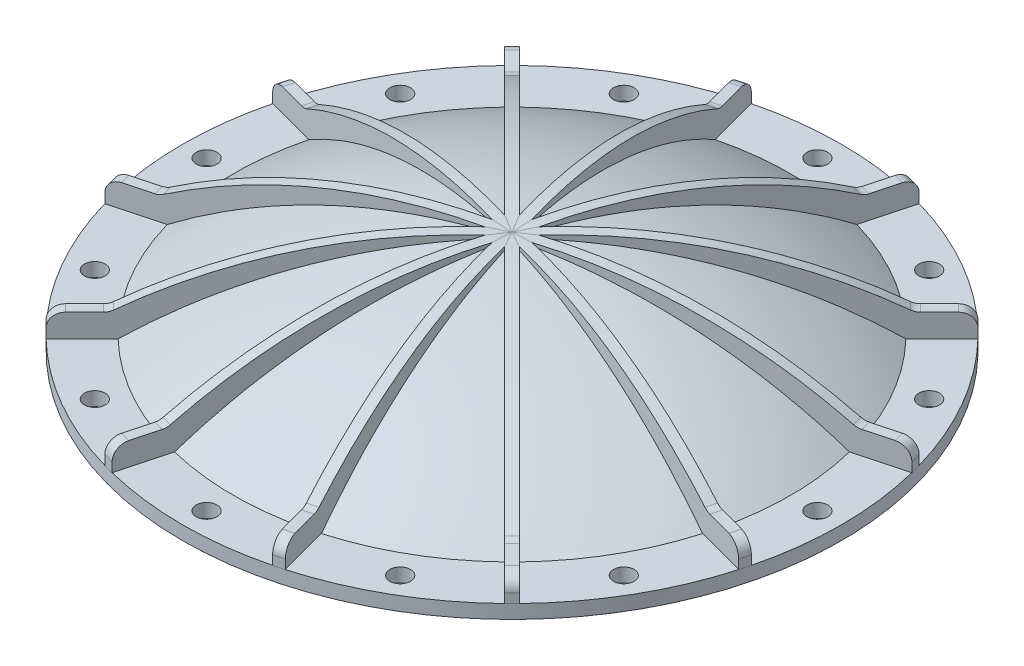
SolidWorks part; units mm, degrees
ref_plane "Front Plane" through (0, 0, 0) normal (0, 0, 1) x (1, 0, 0)
ref_plane "Top Plane" through (0, 0, 0) normal (0, 1, 0) x (1, 0, 0)
ref_plane "Right Plane" through (0, 0, 0) normal (1, 0, 0) x (0, 0, -1)
sketch "Sketch1" plane through (0, 0, 0) normal (0, 0, 1) x (1, 0, 0)
  line L0 (0, 0) -> (0, 65.6866) construction
  line L2 (151.84, 6.6196) -> (128.3759, 6.6196)
  arc A0 (124.8548, 7.6852) -> (2.4084, 46.7854) centre (-4.699, -186.7493) ccw
  arc A1 (128.3759, 6.6196) -> (124.8548, 7.6852) centre (128.3759, 12.9696) cw
  point P9 (126.44, 6.6196)
  dimension "D2" = 6.35
  dimension "D1" = 25.4
revolve "Revolve-Thin2" add sketch "Sketch1" angle 360 about L0
sketch "Sketch2" plane through (0, 0, 0) normal (0, 0, 1) x (1, 0, 0)
  line L0 (2.3304, 46.6898) -> (0, 46.6898)
  line L1 (0, 46.6898) -> (0, 62.1846) construction
revolve "Revolve-Thin3" add sketch "Sketch2" angle 360 about L1
sketch "Sketch4" plane through (0, 0, 0) normal (0, 0, 1) x (1, 0, 0)
  line L0 (0, 0) -> (0, 112.9727) construction
ref_plane "Plane1" through (0, 0, 0) normal (0.2588, 0, 0.9659) x (0.9659, 0, -0.2588)
sketch "Sketch5" plane through (0, 0, 0) normal (0.2588, 0, 0.9659) x (0.9659, 0, -0.2588)
  line L0 (151.84, 12.9696) -> (151.84, 17.2343)
  line L1 (145.49, 23.5843) -> (133.0255, 23.5843)
  line L2 (0, 0) -> (0, 112.9727) construction
  line L3 (151.84, 12.9696) -> (118.132, 12.9696)
  line L4 (151.84, 12.9696) -> (-151.84, 12.9696) construction
  line L5 (118.132, 12.9696) -> (94.1712, 28.0987)
  line L6 (94.1712, 28.0987) -> (45.2078, 45.1143)
  line L7 (45.2078, 45.1143) -> (0, 51.365)
  line L8 (0, 51.365) -> (0, 53.7958)
  arc A0 (0, 53.7958) -> (129.8768, 24.42) centre (16.8415, -173.5386) cw
  arc A1 (151.84, 17.2343) -> (145.49, 23.5843) centre (145.49, 17.2343) ccw
  arc A2 (133.0255, 23.5843) -> (129.8768, 24.42) centre (133.0255, 29.9343) cw
  dimension "D1" = 6.35
extrude "Extrude1" add sketch "Sketch5" along normal mid plane 4.7752
ref_plane "Plane2" through (0, 0, 0) normal (0.5, 0, 0.866) x (0.866, 0, -0.5)
mirror "Mirror1" about plane through (0, 0, 0) normal (0.5, 0, 0.866) of "Extrude1"
pattern_circular "CirPattern1" count 12 over 360 about axis through (0, 0, 0) along (0, 1, 0) of "Mirror1"
ref_plane "Plane3" through (0, 0, 0) normal (1, 0, 0) x (0, 0, -1)
sketch "Sketch6" plane through (0, 0, 0) normal (1, 0, 0) x (0, 0, -1)
  line L0 (0, 12.9696) -> (151.84, 12.9696) construction
  line L2 (30.9141, 12.9696) -> (-30.9141, 12.9696) construction
ref_plane "Plane4" through (0, 12.9696, 0) normal (0, 1, 0) x (-1, 0, 0)
sketch "Sketch7" plane through (0, 12.9696, 0) normal (0, 1, 0) x (-1, 0, 0)
  line L0 (0, 3.4322) -> (0, -140.7332) construction
  circle A0 centre (0, 0) radius 140.7332 construction
hole_wizard "3/8 (0.375) Diameter Hole1" positions "Sketch9" profile "Sketch8" hole size "3/8" standard "Ansi Inch"
sketch "Sketch9" plane through (0, 12.9696, 0) normal (0, 1, 0) x (-1, 0, 0)
  point P1 (0, -140.7332)
sketch "Sketch8" plane through (0, 12.9696, -140.7332) normal (1, 0, 0) x (0, 0, 1)
  line L0 (0, 0) -> (0, 28.2616)
  line L1 (0, 28.2616) -> (4.7625, 25.4)
  line L2 (4.7625, 25.4) -> (4.7625, 0)
  line L5 (4.7625, 0) -> (0, 0)
  line L10 (0, 28.2616) -> (-4.7625, 25.4) construction
  line L11 (0, -6.35) -> (0, 107.95) construction
  dimension "Hole Dia." = 9.525
  dimension "Hole Depth" = 25.4
  dimension "Drill Angle" = 118
pattern_circular "CirPattern2" count 12 over 360 about axis through (0, 0, 0) along (0, 1, 0) of "3/8 (0.375) Diameter Hole1"
